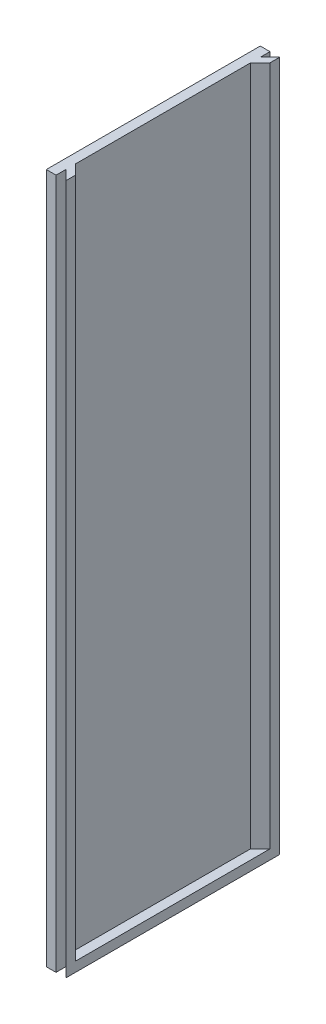
SolidWorks part; units mm, degrees
ref_plane "前视基准面" through (0, 0, 0) normal (0, 0, 1) x (1, 0, 0)
ref_plane "上视基准面" through (0, 0, 0) normal (0, 1, 0) x (1, 0, 0)
ref_plane "右视基准面" through (0, 0, 0) normal (1, 0, 0) x (0, 0, -1)
other "Configuration Table"
sketch "草图2" plane through (0, 0, 0) normal (0, 1, 0) x (1, 0, 0)
  line L0 (-1, 11) -> (0, 11)
  line L1 (-5.1677, 0) -> (26.3219, 0) construction
  line L2 (0, 11) -> (0, 10)
  line L3 (0, 10) -> (1, 11)
  line L4 (1, 11) -> (1, 10)
  line L5 (0, 9) -> (1, 10)
  line L6 (0, -9) -> (1, -10)
  line L7 (1, -11) -> (1, -10)
  line L8 (0, -10) -> (1, -11)
  line L9 (-1, -11) -> (0, -11)
  line L10 (0, 9) -> (0, -9)
  line L11 (0, -10) -> (0, -11)
  line L12 (-1, -11) -> (-1, 11)
  point P5 (0, 0)
  point P15 (0, 0)
  point P16 (0, 0)
  dimension "D1" = 1
  dimension "D2" = 45
  dimension "D3" = 1
  dimension "D4" = 0
  dimension "D5" = 22
  dimension "D6" = 1
extrude "凸台-拉伸1" add sketch "草图2" along normal blind 71
sketch "草图3" plane through (0, 0, 0) normal (0, -1, 0) x (1, 0, 0)
  line L0 (1, 10) -> (1, -10)
  line L1 (1, 10) -> (0, 9) construction
  line L2 (0, 9) -> (0, -9) construction
  line L3 (0, -9) -> (1, -10) construction
  line L4 (1, 10) -> (0, 9)
  line L5 (0, 9) -> (0, -9)
  line L6 (0, -9) -> (1, -10)
extrude "凸台-拉伸2" add sketch "草图3" against normal blind 1
